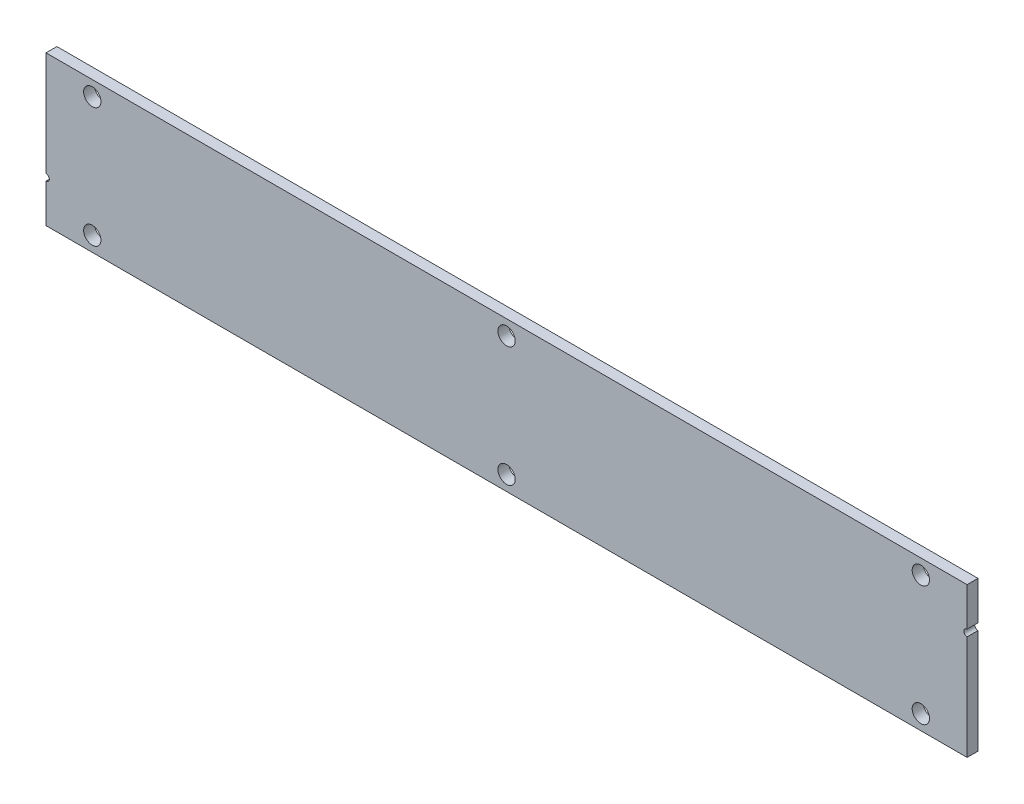
SolidWorks part; units mm, degrees
ref_plane "Front Plane" through (0, 0, 0) normal (0, 0, 1) x (1, 0, 0)
ref_plane "Top Plane" through (0, 0, 0) normal (0, 1, 0) x (1, 0, 0)
ref_plane "Right Plane" through (0, 0, 0) normal (1, 0, 0) x (0, 0, -1)
sketch "Sketch1" plane through (0, 0, 0) normal (0, 0, 1) x (1, 0, 0)
  line L0 (0, -9.1) -> (0, 9.1) construction
  line L1 (-69.85, -11.35) -> (69.85, -11.35)
  line L2 (-69.85, -11.35) -> (-69.85, 11.35)
  line L3 (69.85, -11.35) -> (69.85, 11.35)
  line L4 (-69.85, 11.35) -> (69.85, 11.35)
  line L5 (-69.85, -11.35) -> (69.85, 11.35) construction
  line L6 (69.85, -11.35) -> (-69.85, 11.35) construction
  line L7 (-62.83, -9.1) -> (-62.83, 9.1) construction
  line L8 (62.83, -9.1) -> (62.83, 9.1) construction
  circle A0 centre (0, -9.1) radius 1.3125
  circle A1 centre (0, 9.1) radius 1.3125
  circle A2 centre (-62.83, -9.1) radius 1.3125
  circle A3 centre (-62.83, 9.1) radius 1.3125
  circle A4 centre (62.83, -9.1) radius 1.3125
  circle A5 centre (62.83, 9.1) radius 1.3125
  circle A6 centre (-69.85, -5) radius 0.5
  circle A7 centre (69.85, 5) radius 0.5
  point P4 (0, 0)
  point P7 (0, 0)
  point P15 (-62.83, 0)
  point P20 (62.83, 0)
  dimension "D1" = 2.625
  dimension "D5" = 2.625
  dimension "D8" = 2.625
  dimension "D12" = 1
  dimension "D13" = 1
  dimension "D2" = 18.2
  dimension "D3" = 22.7
  dimension "D4" = 139.7
  dimension "D6" = 18.2
  dimension "D7" = 62.83
  dimension "D9" = 18.2
  dimension "D10" = 62.83
  dimension "D11" = 6.35
  dimension "D14" = 6.35
extrude "Boss-Extrude1" add sketch "Sketch1" along normal blind 1.651 contours A7 L3 L4 L2 A6 L1 A5 A4 A3 A2 A1 A0
